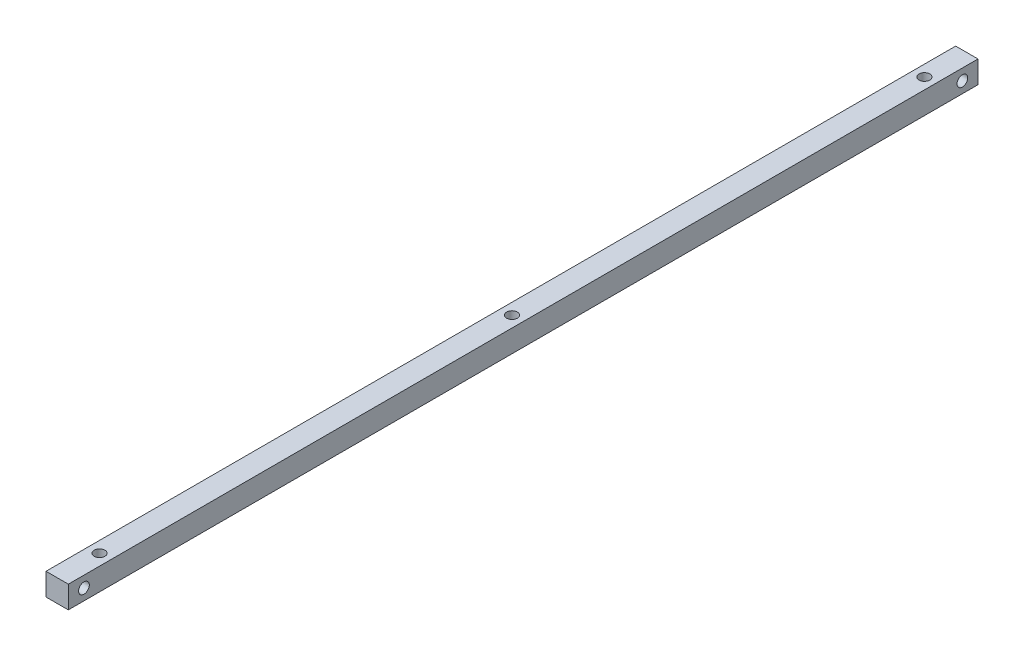
SolidWorks part; units mm, degrees
ref_plane "Alzado" through (0, 0, 0) normal (0, 0, 1) x (1, 0, 0)
ref_plane "Planta" through (0, 0, 0) normal (0, 1, 0) x (1, 0, 0)
ref_plane "Vista lateral" through (0, 0, 0) normal (1, 0, 0) x (0, 0, -1)
sketch "Croquis1" plane through (0, 0, 0) normal (1, 0, 0) x (0, 0, -1)
  line L0 (55, 0) -> (-55, 0) construction
  line L1 (-127.35, -3.125) -> (127.35, -3.125)
  line L2 (-127.35, -3.125) -> (-127.35, 3.125)
  line L3 (-127.35, 3.125) -> (127.35, 3.125)
  line L4 (127.35, -3.125) -> (127.35, 3.125)
  line L5 (0, 55) -> (0, -55) construction
  point P4 (0, -3.125)
  point P5 (-127.35, 0)
  dimension "D1" = 6.25
  dimension "D2" = 254.7
extrude "Saliente-Extruir1" add sketch "Croquis1" along normal mid plane 6.25
sketch "Croquis2" plane through (3.125, 0, 0) normal (1, 0, 0) x (0, 0, -1)
  line L0 (-127.35, 3.125) -> (-127.35, -3.125) construction
  line L1 (-127.35, 0) -> (127.35, 0) construction
  line L2 (127.35, -3.125) -> (127.35, 3.125) construction
  circle A0 centre (-122.975, 0) radius 1.5
  circle A2 centre (122.975, 0) radius 1.5
  point P0 (-127.35, 0)
  point P7 (-122.975, 0)
  point P9 (122.975, 0)
  dimension "D3" = 4.375
  dimension "D1" = 4.375
extrude "Cortar-Extruir1" cut sketch "Croquis2" against normal mid plane 40
sketch "Croquis3" plane through (0, -3.125, 0) normal (0, -1, 0) x (1, 0, 0)
  line L0 (3.125, 127.35) -> (-3.125, 127.35) construction
  line L1 (3.125, -127.35) -> (-3.125, -127.35) construction
  line L2 (3.125, 127.35) -> (3.125, -127.35) construction
  line L3 (0, 127.35) -> (0, -127.35) construction
  line L4 (3.125, 0) -> (-3.125, 0) construction
  line L5 (-3.125, 127.35) -> (-3.125, -127.35) construction
  circle A0 centre (0, 115.475) radius 1.5
  circle A1 centre (0, -115.475) radius 1.5
  circle A2 centre (0, 0) radius 1.5
  point P0 (0, 127.35)
  point P1 (0, -127.35)
  point P4 (3.125, 0)
  point P11 (0, -115.475)
  point P12 (0, 115.475)
  dimension "D2" = 11.875
  dimension "D1" = 11.875
extrude "Cortar-Extruir2" cut sketch "Croquis3" against normal mid plane 60
